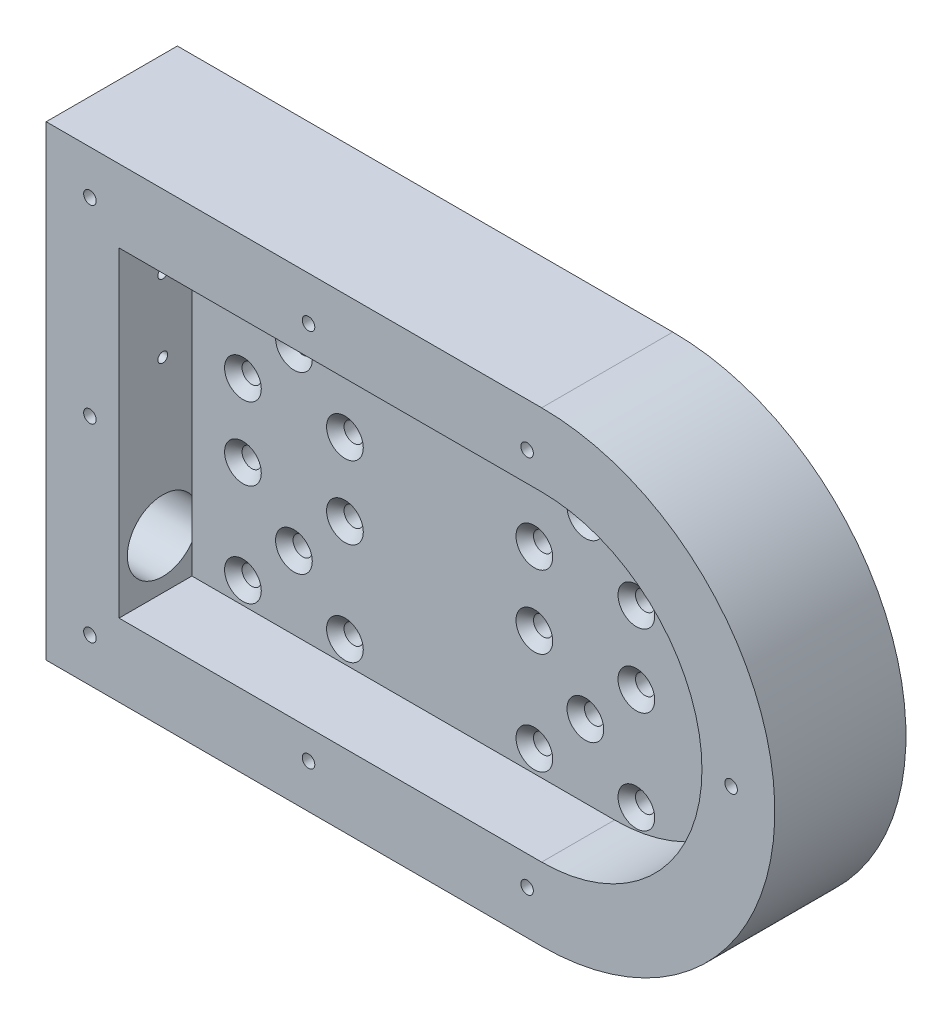
SolidWorks part; units mm, degrees
ref_plane "Front Plane" through (0, 0, 0) normal (0, 0, 1) x (1, 0, 0)
ref_plane "Top Plane" through (0, 0, 0) normal (0, 1, 0) x (1, 0, 0)
ref_plane "Right Plane" through (0, 0, 0) normal (1, 0, 0) x (0, 0, -1)
sketch "Sketch1" plane through (0, 0, 0) normal (0, 0, 1) x (1, 0, 0)
  line L0 (0, 80) -> (-170, 80)
  line L1 (-170, 80) -> (-170, -80)
  line L2 (-170, -80) -> (0, -80)
  arc A0 (0, -80) -> (0, 80) centre (0, 0) ccw
  circle A1 centre (-155, 65) radius 1.5
  circle A2 centre (-80, 65) radius 1.5
  circle A3 centre (-5, 65) radius 1.5
  circle A4 centre (-155, -65) radius 1.5
  circle A5 centre (-80, -65) radius 1.5
  circle A6 centre (-5, -65) radius 1.5
  circle A7 centre (-155, 0) radius 1.5
  circle A8 centre (65, 0) radius 1.5
  point P1 (80, 0)
  dimension "D1" = 250
  dimension "D2" = 80
  dimension "D6" = 65
  dimension "D7" = 220
  dimension "D10" = 3
  dimension "D3" = 75
  dimension "D4" = 75
  dimension "D5" = 65
  dimension "D8" = 15
  dimension "D9" = 15
extrude "Boss-Extrude1" add sketch "Sketch1" along normal mid plane 20
sketch "Sketch6" plane through (0, 0, 10) normal (0, 0, 1) x (1, 0, 0)
  line L0 (0, 55) -> (-145, 55)
  line L1 (-145, 55) -> (-145, -55)
  line L2 (-145, -55) -> (0, -55)
  line L3 (0, 80) -> (-170, 80)
  line L4 (-170, 80) -> (-170, -80)
  line L5 (-170, -80) -> (0, -80)
  line L6 (0, 80) -> (-170, 80)
  line L7 (-170, 80) -> (-170, -80)
  line L8 (-170, -80) -> (0, -80)
  arc A0 (0, -55) -> (0, 55) centre (0, 0) ccw
  arc A1 (0, -80) -> (0, 80) centre (0, 0) ccw
  arc A2 (0, -80) -> (0, 80) centre (0, 0) ccw
  dimension "D1" = 0
  dimension "D2" = 25
extrude "Boss-Extrude2" add sketch "Sketch6" along normal blind 25
hole_wizard "M4 Clearance Hole2" positions "Sketch3" profile "Sketch4" hole size "M4" standard "ANSI Metric" end condition through all
sketch "Sketch3" plane through (0, 0, -10) normal (0, 0, 1) x (1, 0, 0)
  point P0 (-5, -65)
  point P2 (-80, -65)
  point P4 (-155, -65)
  point P6 (-155, 0)
  point P8 (-155, 65)
  point P10 (-80, 65)
  point P12 (-5, 65)
  point P14 (65, 0)
sketch "Sketch4" plane through (-5, -65, -10) normal (1, 0, 0) x (0, 1, 0)
  line L0 (0, 0) -> (0, 45)
  line L1 (0, 45) -> (2.15, 45)
  line L2 (2.15, 45) -> (2.15, 0)
  line L5 (2.15, 0) -> (0, 0)
  line L11 (0, -6.35) -> (0, 107.95) construction
  dimension "Thru Hole Dia." = 4.3
  dimension "Thru Hole Depth" = 45
sketch "Sketch5" plane through (0, 0, 10) normal (0, 0, 1) x (1, 0, 0)
  circle A0 centre (-155, 65) radius 7.5
  circle A1 centre (-80, 65) radius 7.5
  circle A2 centre (-5, 65) radius 7.5
  circle A3 centre (65, 0) radius 7.5
  circle A4 centre (-5, -65) radius 7.5
  circle A5 centre (-80, -65) radius 7.5
  circle A6 centre (-155, -65) radius 7.5
  circle A7 centre (-5, 65) radius 2.15 construction
  circle A8 centre (-80, 65) radius 2.15 construction
  circle A9 centre (-155, 65) radius 2.15 construction
  circle A14 centre (-155, -65) radius 1.65
  circle A15 centre (-80, -65) radius 1.65
  circle A16 centre (-5, -65) radius 1.65
  circle A17 centre (65, 0) radius 1.65
  circle A18 centre (-5, 65) radius 2.15
  circle A19 centre (-80, 65) radius 2.15
  circle A20 centre (-155, 65) radius 2.15
  dimension "D1" = 15
  dimension "D2" = 3.3
hole_wizard "CSK for M6 Flat Head Machine Screw1" positions "Sketch7" profile "Sketch8" countersink size "M6" standard "ANSI Metric" end condition through all
sketch "Sketch7" plane through (0, 0, 10) normal (0, 0, -1) x (-1, 0, 0)
  line L1 (-7.5, 47.5) -> (27.5, 47.5) construction
  line L2 (-7.5, 47.5) -> (-7.5, 12.5) construction
  line L3 (-7.5, 12.5) -> (27.5, 12.5) construction
  line L4 (27.5, 47.5) -> (27.5, 12.5) construction
  line L5 (-7.5, 47.5) -> (27.5, 12.5) construction
  line L6 (-7.5, 12.5) -> (27.5, 47.5) construction
  line L8 (92.5, 47.5) -> (127.5, 47.5) construction
  line L9 (92.5, 47.5) -> (92.5, 12.5) construction
  line L10 (92.5, 12.5) -> (127.5, 12.5) construction
  line L11 (127.5, 47.5) -> (127.5, 12.5) construction
  line L12 (92.5, 47.5) -> (127.5, 12.5) construction
  line L13 (92.5, 12.5) -> (127.5, 47.5) construction
  line L15 (92.5, -12.5) -> (127.5, -12.5) construction
  line L16 (92.5, -12.5) -> (92.5, -47.5) construction
  line L17 (92.5, -47.5) -> (127.5, -47.5) construction
  line L18 (127.5, -12.5) -> (127.5, -47.5) construction
  line L19 (92.5, -12.5) -> (127.5, -47.5) construction
  line L20 (92.5, -47.5) -> (127.5, -12.5) construction
  line L22 (-7.5, -12.5) -> (27.5, -12.5) construction
  line L23 (-7.5, -12.5) -> (-7.5, -47.5) construction
  line L24 (-7.5, -47.5) -> (27.5, -47.5) construction
  line L25 (27.5, -12.5) -> (27.5, -47.5) construction
  line L26 (-7.5, -12.5) -> (27.5, -47.5) construction
  line L27 (-7.5, -47.5) -> (27.5, -12.5) construction
  line L28 (170, 80) -> (170, -80) construction
  point P23 (10, 30)
  point P52 (110, 30)
  point P103 (110, -30)
  point P124 (10, -30)
  point P137 (-7.5, 47.5)
  point P140 (27.5, 47.5)
  point P143 (27.5, 12.5)
  point P146 (-7.5, 12.5)
  point P149 (-7.5, -12.5)
  point P152 (27.5, -12.5)
  point P153 (10, -30)
  point P157 (-7.5, -47.5)
  point P160 (27.5, -47.5)
  point P161 (92.5, -47.5)
  point P165 (92.5, -12.5)
  point P168 (127.5, -12.5)
  point P171 (127.5, -47.5)
  point P174 (127.5, 12.5)
  point P177 (127.5, 47.5)
  point P180 (92.5, 47.5)
  point P183 (92.5, 12.5)
  dimension "D1" = 35
  dimension "D2" = 35
  dimension "D3" = 100
  dimension "D4" = 60
  dimension "D5" = 60
  dimension "D6" = 30
sketch "Sketch8" plane through (-92.5, 12.5, 10) normal (1, 0, 0) x (0, -1, 0)
  line L0 (0, 0) -> (0, 20)
  line L1 (0, 20) -> (3.3, 20)
  line L2 (3.3, 20) -> (3.3, 3)
  line L3 (3.3, 3) -> (6.3, 0)
  line L5 (6.3, 0) -> (0, 0)
  line L6 (-3.3, 3) -> (-6.3, 0) construction
  line L11 (0, -6.35) -> (0, 107.95) construction
  dimension "Thru Hole Dia." = 6.6
  dimension "Thru Hole Depth" = 20
  dimension "Near C'Sink Dia." = 12.6
  dimension "Near C'Sink Angle" = 90
sketch "Sketch9" plane through (-170, 0, 0) normal (-1, 0, 0) x (0, 0, 1)
  line L0 (35, 80) -> (35, -80) construction
  circle A0 centre (20, -38) radius 12.15
  dimension "D1" = 24.3
  dimension "D2" = 15
  dimension "D3" = 17
extrude "Cut-Extrude1" cut sketch "Sketch9" against normal up to surface (25 mm away) up to face at (-145, 0, 22.5)
sketch "Sketch10" plane through (-170, 0, 0) normal (-1, 0, 0) x (0, 0, 1)
  line L1 (-10, 80) -> (-10, -80) construction
  line L2 (35, 80) -> (-10, 80) construction
  circle A0 centre (20, 40) radius 1.5
  circle A1 centre (20, 15) radius 1.5
  dimension "D1" = 3
  dimension "D2" = 3
  dimension "D3" = 25
  dimension "D4" = 40
  dimension "D5" = 30
hole_wizard "M3 Clearance Hole5" positions "Sketch11" profile "Sketch12" hole size "M3" standard "ANSI Metric"
sketch "Sketch11" plane through (-170, 0, 0) normal (-1, 0, 0) x (0, 0, 1)
  circle A2 centre (20, 15) radius 1.5
  circle A3 centre (20, 15) radius 1.5
  circle A6 centre (20, 40) radius 1.5
  circle A7 centre (20, 40) radius 1.5
  point P5 (20, 15)
  point P12 (20, 40)
  dimension "D1" = 0
  dimension "D2" = 0
sketch "Sketch12" plane through (-170, 15, 20) normal (0, 1, 0) x (0, 0, 1)
  line L0 (0, 0) -> (0, 25)
  line L1 (0, 25) -> (1.7, 25)
  line L2 (1.7, 25) -> (1.7, 0)
  line L5 (1.7, 0) -> (0, 0)
  line L11 (0, -6.35) -> (0, 107.95) construction
  dimension "Thru Hole Dia." = 3.4
  dimension "Thru Hole Depth" = 25
